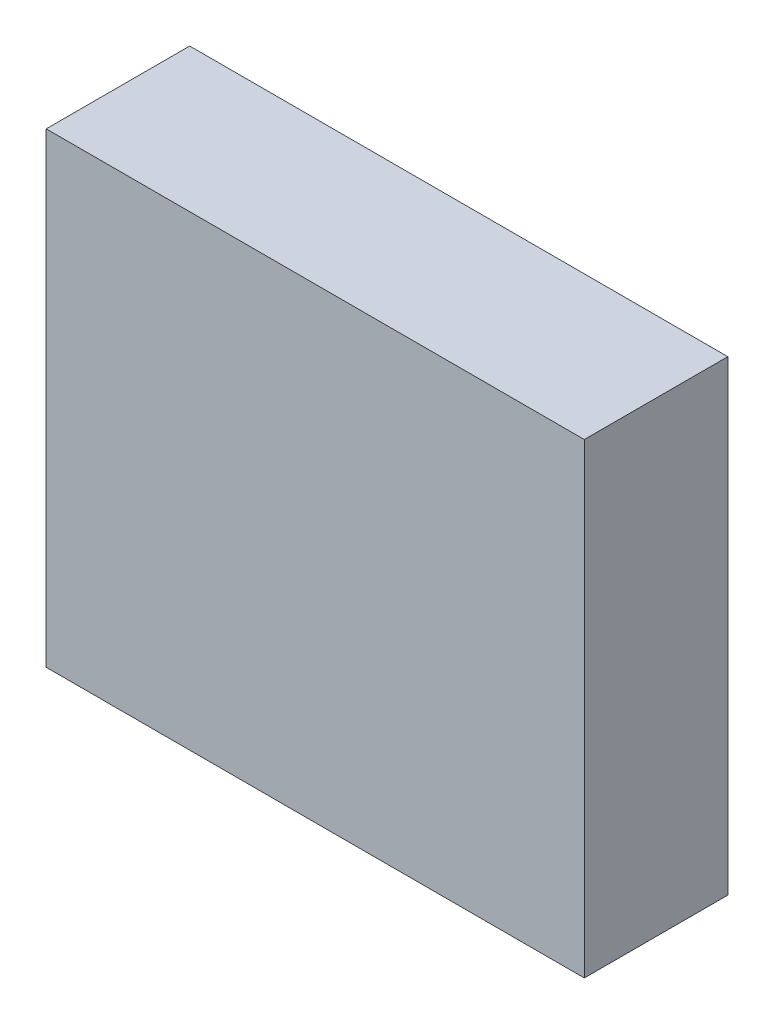
SolidWorks part; units mm, degrees
ref_plane "Plan de face" through (0, 0, 0) normal (0, 0, 1) x (1, 0, 0)
ref_plane "Plan de dessus" through (0, 0, 0) normal (0, 1, 0) x (1, 0, 0)
ref_plane "Plan de droite" through (0, 0, 0) normal (1, 0, 0) x (0, 0, -1)
sketch "Esquisse2" plane through (0, 0, 0) normal (0, 0, 1) x (1, 0, 0)
  line L1 (-37.5, -32.5) -> (37.5, -32.5)
  line L2 (-37.5, -32.5) -> (-37.5, 32.5)
  line L3 (-37.5, 32.5) -> (37.5, 32.5)
  line L4 (37.5, -32.5) -> (37.5, 32.5)
  line L5 (-37.5, -32.5) -> (37.5, 32.5) construction
  line L6 (-37.5, 32.5) -> (37.5, -32.5) construction
  point P0 (0, 0)
  dimension "D1" = 65
  dimension "D2" = 75
extrude "Boss.-Extru.1" add sketch "Esquisse2" along normal blind 20 contours L3 L4 L1 L2
